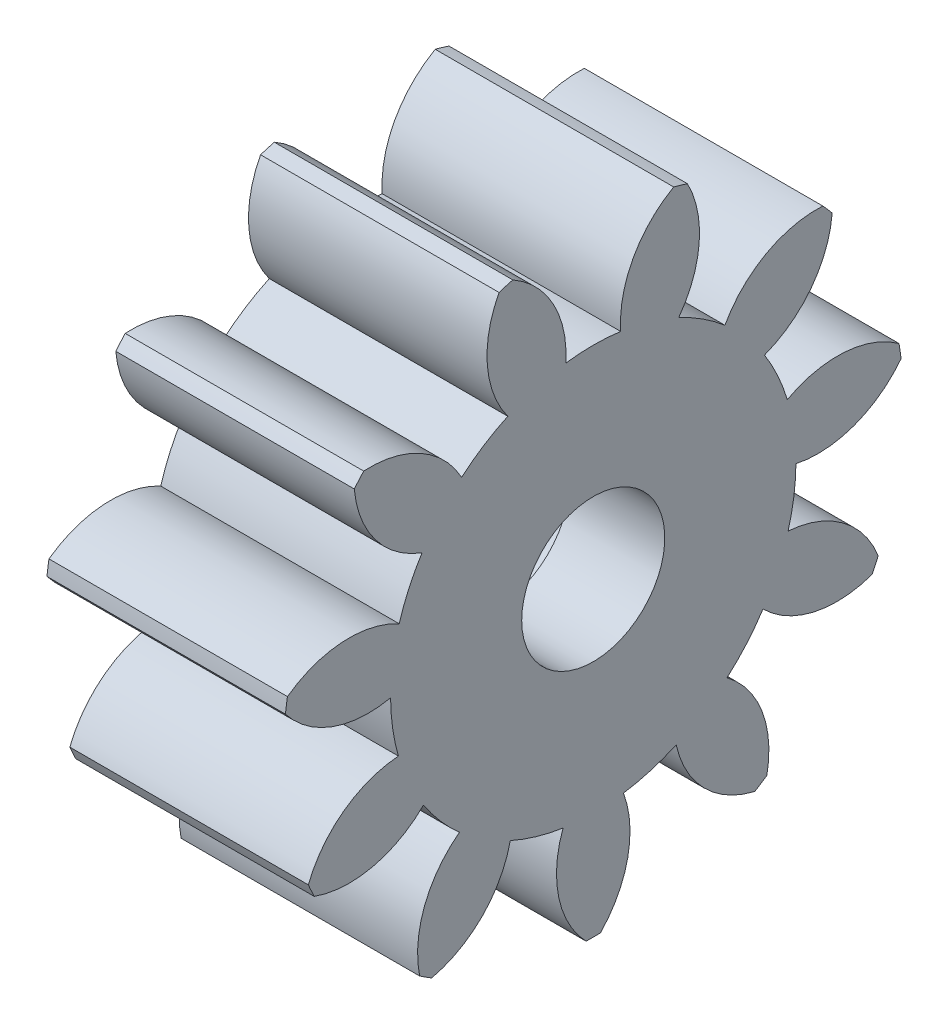
SolidWorks part; units mm, degrees
ref_plane "Plane1" through (0, 0, 0) normal (0, 0, 1) x (1, 0, 0)
ref_plane "Plane2" through (0, 0, 0) normal (0, 1, 0) x (1, 0, 0)
ref_plane "Plane3" through (0, 0, 0) normal (1, 0, 0) x (0, 0, -1)
sketch "HoldingSke" plane through (0, 0, 0) normal (0, 1, 0) x (1, 0, 0)
  line L0 (0, 0) -> (0.9816, -0.1908)
  line L1 (-15, 0) -> (100, 0) construction
  line L2 (0, 0) -> (-2.1039, 2.3779)
  line L3 (0, 0) -> (-11.863, 4.5341)
  line L4 (0, 0) -> (8.4773, 1.6478)
  line L5 (0, 0) -> (-46.8476, -17.4728)
  line L6 (0, 0) -> (-4.1448, -2.7965)
  line L7 (-2.1039, 2.3779) -> (8.6586, 51.2059)
  line L8 (-76.2, 54.61) -> (-75.7, 54.61)
  line L9 (-71.009, 38.7566) -> (-53.1078, 45.2721)
  line L10 (-76.2, 71.12) -> (104.1128, 71.12)
  line L11 (0, 0) -> (-5, 0)
  line L12 (-76.2, 101.6) -> (-76.162, 101.6)
  line L13 (24.9733, 27.94) -> (52.9518, 28.4284)
  line L14 (24.9733, 27.94) -> (24.9743, 27.94)
  line L15 (24.9733, 27.94) -> (100.4006, 29.5858)
  line L16 (-63.627, -1) -> (-12.827, -1)
  circle A0 centre (0, 0) radius 1.5
  circle A1 centre (0, 0) radius 4.249
  circle A2 centre (0, 0) radius 37.5
  circle A3 centre (0, 0) radius 1.5
  dimension "MHD" = 8.498
  dimension "Hub_dia" = 75
  dimension "Bore" = 3
  dimension "MBD" = 3
  dimension "Num_teeth" = 11
  dimension "Pitch" = 1
  dimension "Overall_len" = 50
  dimension "Show_teeth" = 11
  dimension "Thickness" = 5
  dimension "OAL" = 50.0001
  dimension "T_dim" = 0.5
  dimension "Ap" = 20
  dimension "H" = 19.05
  dimension "Pitch_radius" = 180.3128
  dimension "Width" = 5
  dimension "Backlash" = 0.038
  dimension "Addendum_fac" = 1
  dimension "Dedendum_fac" = 1.25
  dimension "Clearance_fac" = 0.25
  dimension "Dedendum_add" = 0.001
  dimension "Module" = 1
sketch "BasProSke" plane through (0, 0, 0) normal (0, 1, 0) x (1, 0, 0)
  line L0 (-10, 0) -> (60, 0) construction
  line L1 (0, 0) -> (0, 6.5)
  line L2 (0, 0) -> (5, 0)
  line L3 (5, 0) -> (5, 6.5)
  line L4 (5, 6.5) -> (0, 6.5)
  dimension "Thickness" = 5
  dimension "Diameter" = 13
revolve "Base-Revolve" add sketch "BasProSke" angle 360 about L0
sketch "TooCutSke" plane through (0, 0, 0) normal (1, 0, 0) x (0, 0, -1)
  line L1 (0, 0) -> (0, 107) construction
  line L2 (0, 0) -> (-0.8491, 5.4341) construction
  line L3 (0, 0) -> (-3.0727, 10.4645) construction
  line L4 (-0.8491, 5.4341) -> (-1.5363, 5.2323) construction
  arc A0 (0.576, 4.2098) -> (-0.576, 4.2098) centre (0, 0) ccw
  arc A1 (1.7187, 6.295) -> (-1.7187, 6.295) centre (0, 0) ccw
  circle A2 centre (0, 0) radius 5.5 construction
  circle A3 centre (0, 0) radius 5.1683 construction
  arc A4 (-0.576, 4.2098) -> (-1.7187, 6.295) centre (-2.7707, 4.3629) ccw
  arc A5 (1.7187, 6.295) -> (0.576, 4.2098) centre (2.7707, 4.3629) ccw
  dimension "Root_dia" = 8.498
  dimension "Overcut_dia" = 13.0508
  dimension "Pitch_dia" = 11
  dimension "Base_dia" = 10.3366
  dimension "Flank_rad" = 2.2
  dimension "Half_ang" = 16.364
  dimension "Half_CT" = 0.7162
extrude "ToothCut" cut sketch "TooCutSke" along normal through all
fillet "Breaks" [suppressed] radius 0.02
fillet "RootFillets" [suppressed] radius 0.251
pattern_circular "TeethCuts" count 11 every 32.727 about axis through (-10, 0, 0) along (1, 0, 0) of "ToothCut", "RootFillets", "Breaks"
sketch "HubNeaOneSke" plane through (0, 0, 0) normal (-1, 0, 0) x (0, 0, 1)
  circle A0 centre (0, 0) radius 4.249
  dimension "Diameter" = 8.498
extrude "HubNearOne" [suppressed] add sketch "HubNeaOneSke" along normal blind 45.0001
sketch "HubNeaBotSke" plane through (0, 0, 0) normal (-1, 0, 0) x (0, 0, 1)
  circle A0 centre (0, 0) radius 4.249
  dimension "Diameter" = 8.498
extrude "HubNearBoth" [suppressed] add sketch "HubNeaBotSke" along normal blind 22.5
ref_plane "FarPln" through (5, 0, 0) normal (1, 0, 0) x (0, 0, -1)
sketch "HubFarSke" plane through (5, 0, 0) normal (1, 0, 0) x (0, 0, -1)
  circle A0 centre (0, 0) radius 4.249
  dimension "Diameter" = 8.498
extrude "HubFar" [suppressed] add sketch "HubFarSke" along normal blind 22.5
sketch "BorSke" plane through (0, 0, 0) normal (1, 0, 0) x (0, 0, -1)
  circle A0 centre (0, 0) radius 1.5
  dimension "Diameter" = 3
extrude "Bore" cut sketch "BorSke" along normal mid plane 100.0001
sketch "KeySke" plane through (0, 0, 0) normal (1, 0, 0) x (0, 0, -1)
  line L0 (-0.6, 0) -> (-0.6, 2)
  line L1 (-0.6, 2) -> (0.6, 2)
  line L2 (0.6, 2) -> (0.6, 0)
  line L3 (0, 0) -> (0, 34) construction
  line L4 (-0.6, 0) -> (0.6, 0)
  dimension "Offset" = 2
  dimension "Width" = 1.2
extrude "Keyway" [suppressed] cut sketch "KeySke" along normal mid plane 100.0001
pattern_circular "Keyway2" [suppressed] count 2 every 90 about axis through (-10, 0, 0) along (1, 0, 0)
sketch "Esquisse1" plane through (0, 0, 0) normal (-1, 0, 0) x (0, 0, 1)
  circle A0 centre (0, 0) radius 2.75
  dimension "D1" = 5.5
extrude "Enlèv. mat.-Extru.1" cut sketch "Esquisse1" against normal blind 3
equation "' \"Module@HoldingSke\" = 6.35"
equation "' \"Num_teeth@HoldingSke\" = 12"
equation "' \"Ap@HoldingSke\" =  20"
equation "' \"Ap@HoldingSke\" = 20"
equation "' \"Width@HoldingSke\" = 0.5 * 25.4"
equation "' \"Hub_dia@HoldingSke\"= 1 * 25.4"
equation "' \"Hub_dia@HoldingSke\" = 1 * 25.4"
equation "' \"Overall_len@HoldingSke\" = 1.0 * 25.4"
equation "' \"Bore@HoldingSke\" = 0.75 * 25.4"
equation "' \"T_dim@HoldingSke\" = 0.1 * 25.4"
equation "' \"Width@KeySke\" = 0.25 * 25.4"
equation "' \"Show_teeth@HoldingSke\" = 13"
equation "' \"Backlash@HoldingSke\" = 0.009 * 25.4"
equation "' \"Addendum_fac@HoldingSke\" = 1.0"
equation "' \"Dedendum_fac@HoldingSke\" = 1.25"
equation "' \"Dedendum_add@HoldingSke\" = 0.00005 * 25.4"
equation "' \"Clearance_fac@HoldingSke\" = 0.25"
equation "\"Pitch@HoldingSke\" = 1 / \"Module@HoldingSke\""
equation "\"Overcut_dia@TooCutSke\" = (\"Num_teeth@HoldingSke\" + 2 * \"Addendum_fac@HoldingSke\") / \"Pitch@HoldingSke\" + 0.002 * 25.4"
equation "\"Pitch_dia@TooCutSke\" = \"Num_teeth@HoldingSke\" / \"Pitch@HoldingSke\""
equation "\"Base_dia@TooCutSke\" = \"Num_teeth@HoldingSke\" / \"Pitch@HoldingSke\" * cos((\"Ap@HoldingSke\"  * 3.14159265 / 180))"
equation "\"Root_dia@TooCutSke\" = (\"Num_teeth@HoldingSke\" + 2) / \"Pitch@HoldingSke\" - 2 * (\"Addendum_fac@HoldingSke\" + \"Dedendum_fac@HoldingSke\") / \"Pitch@HoldingSke\" - \"Dedendum_add@HoldingSke\" * 2"
equation "\"Half_ang@TooCutSke\" = 180 / \"Num_teeth@HoldingSke\""
equation "\"Half_CT@TooCutSke\" = \"Num_teeth@HoldingSke\" / \"Pitch@HoldingSke\" * sin((3.14159265 / 2 / \"Num_teeth@HoldingSke\")) / 2 - 7 * \"Backlash@HoldingSke\" / 4"
equation "\"Flank_rad@TooCutSke\" = \"Num_teeth@HoldingSke\" / \"Pitch@HoldingSke\" / 5"
equation "\"Radius@RootFillets\" = \"Clearance_fac@HoldingSke\" / \"Pitch@HoldingSke\" + \"Dedendum_add@HoldingSke\""
equation "\"Break_rad@Breaks\" = 0.02 / \"Pitch@HoldingSke\""
equation "\"Thickness@HoldingSke\" = \"Width@HoldingSke\""
equation "\"OAL@HoldingSke\" = \"Thickness@HoldingSke\""
equation "\"MHD@HoldingSke\" = (\"Num_teeth@HoldingSke\" + 2) / \"Pitch@HoldingSke\" - 2 * (\"Addendum_fac@HoldingSke\" + \"Dedendum_fac@HoldingSke\")  / \"Pitch@HoldingSke\" - \"Dedendum_add@HoldingSke\" * 2"
equation "\"MBD@HoldingSke\" = (\"Num_teeth@HoldingSke\" + 2) / \"Pitch@HoldingSke\" - 2 * (\"Addendum_fac@HoldingSke\" + \"Dedendum_fac@HoldingSke\")  / \"Pitch@HoldingSke\" - \"Dedendum_add@HoldingSke\" * 2 - 0.002 * 25.4"
equation "\"MHD@HoldingSke\" = ((sgn( \"MHD@HoldingSke\" - \"Hub_dia@HoldingSke\" )-1)*( \"MHD@HoldingSke\" - \"Hub_dia@HoldingSke\" ))/-2+ \"Hub_dia@HoldingSke\""
equation "\"MBD@HoldingSke\" = ((sgn( \"MBD@HoldingSke\" - \"Bore@HoldingSke\" )-1)*( \"MBD@HoldingSke\" - \"Bore@HoldingSke\" ))/-2+ \"Bore@HoldingSke\""
equation "\"OAL@HoldingSke\" = ((sgn( \"OAL@HoldingSke\" - \"Overall_len@HoldingSke\" )+1)*( \"OAL@HoldingSke\" - \"Overall_len@HoldingSke\" ))/2 + \"Overall_len@HoldingSke\" + 0.000002 * 25.4"
equation "\"Num_teeth@TeethCuts\" = int( \"Show_teeth@HoldingSke\" ) + 1"
equation "\"Num_teeth@TeethCuts\" = ((sgn( \"Num_teeth@TeethCuts\" - \"Num_teeth@HoldingSke\" )-1)*( \"Num_teeth@TeethCuts\" - \"Num_teeth@HoldingSke\" ))/-2+ \"Num_teeth@HoldingSke\""
equation "\"Num_teeth@TeethCuts\" = ((sgn( \"Num_teeth@TeethCuts\" - 2.0)+1)*( \"Num_teeth@TeethCuts\" - 2.0))/2 +2.0"
equation "\"Angle@TeethCuts\" = 360.0 / \"Num_teeth@HoldingSke\""
equation "\"Diameter@BasProSke\" = (\"Num_teeth@HoldingSke\" + 2 * \"Addendum_fac@HoldingSke\") / \"Pitch@HoldingSke\""
equation "\"Thickness@BasProSke\"  = \"Thickness@HoldingSke\""
equation "' \"Fillet_rad@BasProSke\" =  \"Thickness@HoldingSke\" * 0.05"
equation "' \"Fillet_rad@BasProSke\" = \"Thickness@HoldingSke\" * 0.05"
equation "\"MHD@HoldingSke\" = ((sgn( \"MHD@HoldingSke\" - \"Root_dia@TooCutSke\" )-1)*( \"MHD@HoldingSke\" - \"Root_dia@TooCutSke\" ))/-2+ \"Root_dia@TooCutSke\""
equation "\"Diameter@HubNeaOneSke\" = \"MHD@HoldingSke\""
equation "\"Length@HubNearOne\" = \"OAL@HoldingSke\" - \"Thickness@BasProSke\""
equation "\"Diameter@HubNeaBotSke\" = \"MHD@HoldingSke\""
equation "\"Length@HubNearBoth\" = ( \"OAL@HoldingSke\" - \"Thickness@BasProSke\" ) / 2.0"
equation "\"Thickness@FarPln\" = \"Thickness@BasProSke\""
equation "\"Diameter@HubFarSke\" = \"MHD@HoldingSke\""
equation "\"Length@HubFar\" = ( \"OAL@HoldingSke\" - \"Thickness@BasProSke\" ) / 2.0"
equation "\"Diameter@BorSke\" = \"MBD@HoldingSke\""
equation "\"D1@Bore\" = \"OAL@HoldingSke\" * 2.0"
equation "\"D1@Keyway\" = \"OAL@HoldingSke\" * 2.0"
equation "\"Offset@KeySke\" = \"T_dim@HoldingSke\" + \"MBD@HoldingSke\" / 2.0"
